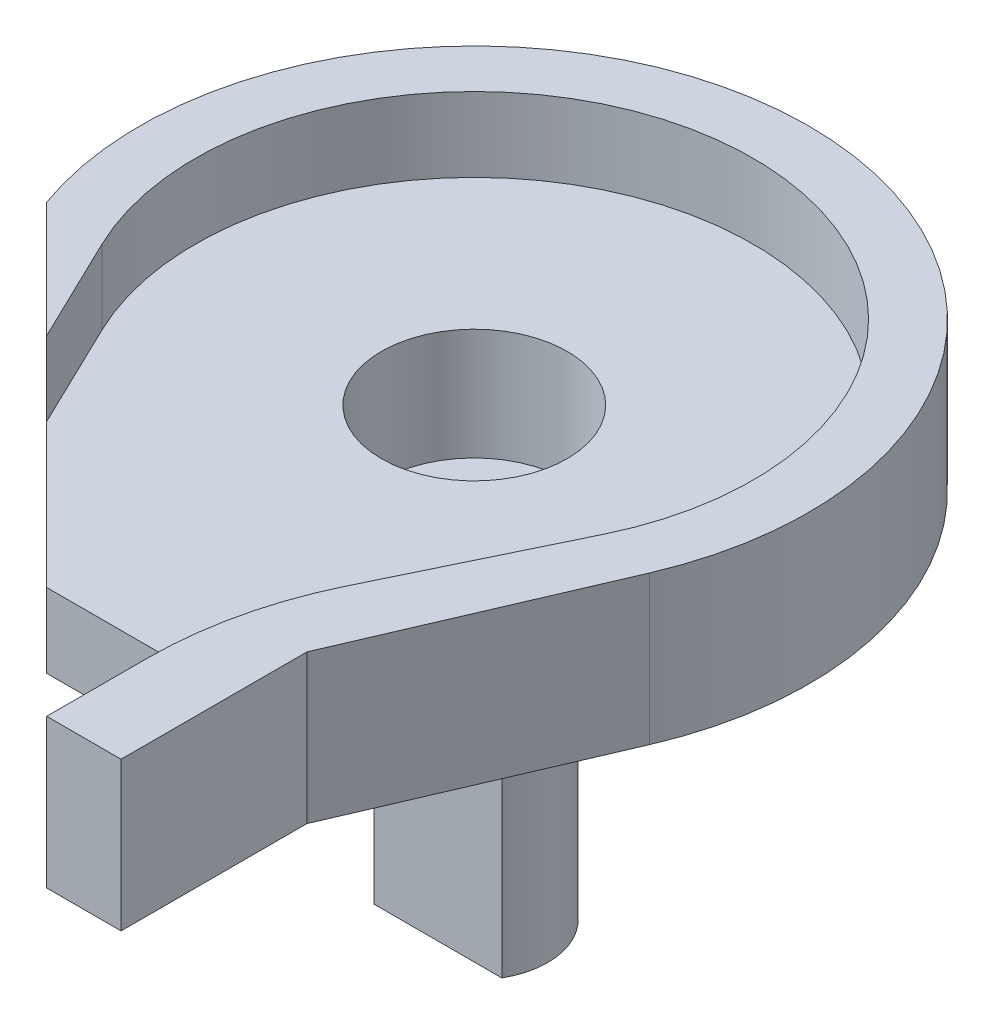
SolidWorks part; units mm, degrees
ref_plane "Front Plane" through (0, 0, 0) normal (0, 0, 1) x (1, 0, 0)
ref_plane "Top Plane" through (0, 0, 0) normal (0, 1, 0) x (1, 0, 0)
ref_plane "Right Plane" through (0, 0, 0) normal (1, 0, 0) x (0, 0, -1)
sketch "Sketch1" plane through (0, 0, 0) normal (0, 1, 0) x (1, 0, 0)
  line L1 (-8.2695, -3.5518) -> (-5.5, -10)
  line L2 (-5.5, -10) -> (5.5, -10)
  line L3 (5.5, -10) -> (8.2695, -3.5518)
  arc A0 (8.2695, -3.5518) -> (-8.2695, -3.5518) centre (0, 0) ccw
  point P12 (0, -10)
  dimension "D1" = 18
  dimension "D2" = 11
  dimension "D3" = 10
extrude "Boss-Extrude1" add sketch "Sketch1" along normal blind 4
sketch "Sketch2" plane through (0, 4, 0) normal (0, 1, 0) x (1, 0, 0)
  line L0 (-6.7539, -3.2611) -> (-3.5, -10)
  line L1 (-5.5, -10) -> (5.5, -10) construction
  line L2 (3.5, -10) -> (6.7539, -3.2611)
  line L3 (-3.5, -10) -> (3.5, -10)
  arc A0 (6.7539, -3.2611) -> (-6.7539, -3.2611) centre (0, 0) ccw
  point P9 (0, -10)
  dimension "D1" = 15
  dimension "D2" = 7
extrude "Cut-Extrude1" cut sketch "Sketch2" against normal blind 2
sketch "Sketch3" plane through (0, 0, 0) normal (0, -1, 0) x (1, 0, 0)
  line L0 (-1.7176, 0.975) -> (1.7176, 0.975)
  line L1 (-5.5, 10) -> (5.5, 10) construction
  line L2 (-2.9588, -1.975) -> (3.9837, -1.975) construction
  arc A0 (-1.7176, 0.975) -> (1.7176, 0.975) centre (0, 0) ccw
  dimension "D1" = 3.95
  dimension "D2" = 2.95
extrude "Boss-Extrude2" add sketch "Sketch3" along normal blind 10
sketch "Sketch4" plane through (0, 0, 0) normal (0, -1, 0) x (1, 0, 0)
  circle A0 centre (0, 0) radius 3
  dimension "D1" = 6
extrude "Boss-Extrude3" add sketch "Sketch4" along normal blind 4
sketch "Sketch5" plane through (0, 2, 0) normal (0, 1, 0) x (1, 0, 0)
  circle A0 centre (0, 0) radius 2.5
  dimension "D1" = 5
extrude "Cut-Extrude2" cut sketch "Sketch5" against normal blind 3
chamfer "Chamfer1" distance 1 angle 45 2 edges at (0, -4, -3) (0, 0, 3)
sketch "Sketch6" plane through (0, 0, 10) normal (0, 0, 1) x (1, 0, 0)
  line L1 (3.5, 4) -> (5.5, 4)
  line L2 (3.5, 4) -> (3.5, 0)
  line L3 (3.5, 0) -> (5.5, 0)
  line L4 (5.5, 4) -> (5.5, 0)
extrude "Boss-Extrude4" add sketch "Sketch6" along normal blind 5
fillet "Fillet1" radius 10 1 edges at (3.5, 3, 10)
sketch "Sketch8" plane through (0, 0, 0) normal (0, -1, 0) x (1, 0, 0)
  line L0 (-5.5, 10) -> (-1.5, 10)
  line L1 (-5.5, 10) -> (3.5, 10) construction
  line L2 (-1.5, 10) -> (-8.5114, 2.9886)
  line L3 (-8.2695, 3.5518) -> (-5.5, 10) construction
  line L4 (-8.5114, 2.9886) -> (-5.5, 10)
  dimension "D1" = 45
  dimension "D2" = 4
extrude "Cut-Extrude3" cut sketch "Sketch8" against normal blind 10
mirror "Mirror1" [suppressed]
delete or keep bodies "Body-Delete/Keep 1" [suppressed] type delete bodies bodies 107
